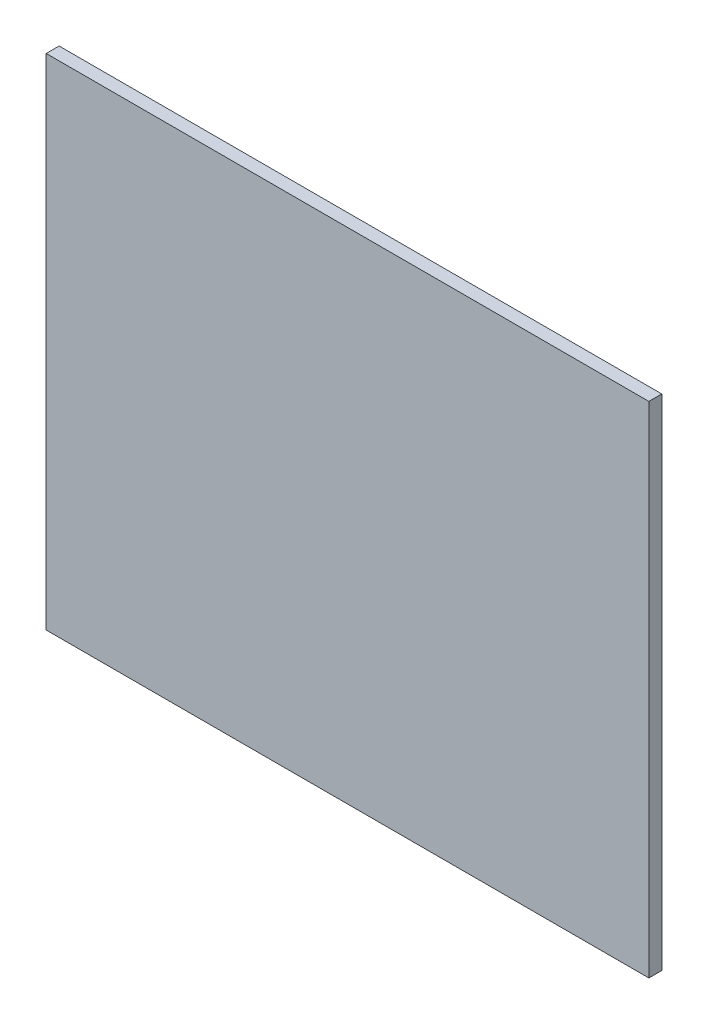
SolidWorks part; units mm, degrees
material "AISI 1020"
ref_plane "Ön Düzlem" through (0, 0, 0) normal (0, 0, 1) x (1, 0, 0)
ref_plane "Üst Düzlem" through (0, 0, 0) normal (0, 1, 0) x (1, 0, 0)
ref_plane "Sağ Düzlem" through (0, 0, 0) normal (1, 0, 0) x (0, 0, -1)
sketch "Çizim1" plane through (0, 0, 0) normal (0, 0, 1) x (1, 0, 0)
  line L1 (0, 0) -> (700, 0)
  line L2 (0, 0) -> (0, 580)
  line L3 (0, 580) -> (700, 580)
  line L4 (700, 0) -> (700, 580)
  dimension "D1" = 700
  dimension "D2" = 580
extrude "Yükseklik-Ekstrüzyon1" add sketch "Çizim1" along normal blind 15
